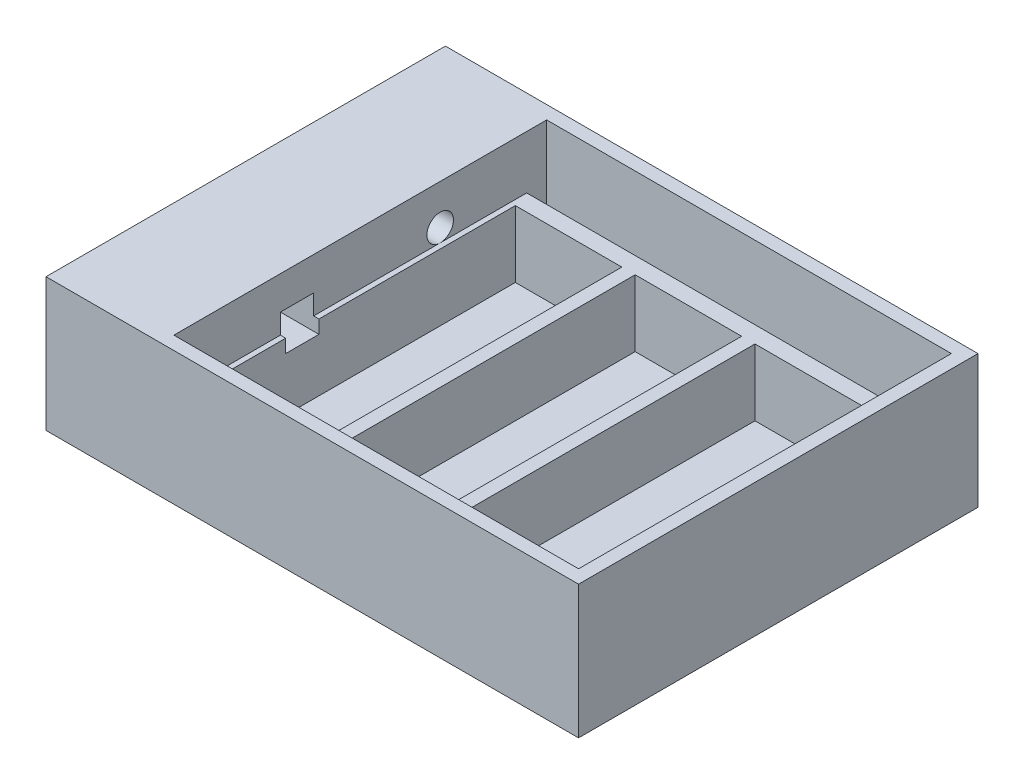
SolidWorks part; units mm, degrees
ref_plane "Front Plane" through (0, 0, 0) normal (0, 0, 1) x (1, 0, 0)
ref_plane "Top Plane" through (0, 0, 0) normal (0, 1, 0) x (1, 0, 0)
ref_plane "Right Plane" through (0, 0, 0) normal (1, 0, 0) x (0, 0, -1)
sketch "Sketch1" plane through (0, 0, 0) normal (0, 1, 0) x (1, 0, 0)
  line L1 (-44.8597, 34.7202) -> (56.7403, 34.7202)
  line L2 (-44.8597, 34.7202) -> (-44.8597, -41.4798)
  line L3 (-44.8597, -41.4798) -> (56.7403, -41.4798)
  line L4 (56.7403, 34.7202) -> (56.7403, -41.4798)
  dimension "D1" = 76.2
  dimension "D2" = 101.6
extrude "Boss-Extrude1" add sketch "Sketch1" along normal blind 25.4
sketch "Sketch2" plane through (0, 25.4, 0) normal (0, 1, 0) x (1, 0, 0)
  line L0 (-44.8597, -41.4798) -> (56.7403, -41.4798) construction
  line L1 (-23.0045, 32.1802) -> (54.2003, 32.1802)
  line L2 (-23.0045, 32.1802) -> (-23.0045, -38.9398)
  line L3 (-23.0045, -38.9398) -> (54.2003, -38.9398)
  line L4 (54.2003, 32.1802) -> (54.2003, -38.9398)
  line L5 (56.7403, 34.7202) -> (-44.8597, 34.7202) construction
  line L6 (56.7403, -41.4798) -> (56.7403, 34.7202) construction
  dimension "D1" = 2.54
  dimension "D2" = 2.54
  dimension "D3" = 2.54
extrude "Cut-Extrude1" cut sketch "Sketch2" against normal blind 22.86
sketch "Sketch3" plane through (0, 2.54, 0) normal (0, 1, 0) x (1, 0, 0)
  line L0 (56.7403, -41.4798) -> (56.7403, 34.7202) construction
  line L1 (-23.0045, 28.3702) -> (50.3903, 28.3702)
  line L2 (-23.0045, 28.3702) -> (-23.0045, -35.1298)
  line L3 (-23.0045, -35.1298) -> (50.3903, -35.1298)
  line L4 (50.3903, 28.3702) -> (50.3903, -35.1298)
  line L5 (56.7403, 34.7202) -> (-44.8597, 34.7202) construction
  line L6 (-44.8597, -41.4798) -> (56.7403, -41.4798) construction
  line L7 (-23.0045, 32.1802) -> (-23.0045, -38.9398) construction
  dimension "D1" = 6.35
  dimension "D2" = 6.35
  dimension "D3" = 6.35
  dimension "D4" = 0
extrude "Boss-Extrude3" add sketch "Sketch3" along normal blind 12.7
sketch "Sketch4" plane through (-44.8597, 0, 0) normal (-1, 0, 0) x (0, 0, 1)
  line L0 (-34.7202, 25.4) -> (-34.7202, 0) construction
  line L1 (-15.6702, 21.59) -> (22.4298, 21.59)
  line L2 (-15.6702, 21.59) -> (-15.6702, 6.35)
  line L3 (-15.6702, 6.35) -> (22.4298, 6.35)
  line L4 (22.4298, 21.59) -> (22.4298, 6.35)
  line L5 (-34.7202, 0) -> (41.4798, 0) construction
  dimension "D1" = 19.05
  dimension "D2" = 38.1
  dimension "D3" = 15.24
  dimension "D4" = 6.35
extrude "Cut-Extrude2" cut sketch "Sketch4" against normal blind 6.35
sketch "Sketch7" plane through (-44.8597, 0, 0) normal (-1, 0, 0) x (0, 0, 1)
  line L0 (22.4298, 21.59) -> (-15.6702, 21.59) construction
  line L1 (-15.6702, 21.59) -> (-15.6702, 6.35) construction
  circle A0 centre (-11.8602, 17.78) radius 2.5355
  dimension "D1" = 3.81
  dimension "D2" = 3.81
extrude "Cut-Extrude3" cut sketch "Sketch7" against normal blind 22.86
sketch "Sketch8" plane through (-38.5097, 0, 0) normal (-1, 0, 0) x (0, 0, 1)
  line L0 (22.4298, 21.59) -> (-15.6702, 21.59) construction
  line L1 (12.2698, 19.05) -> (18.6198, 19.05)
  line L2 (12.2698, 19.05) -> (12.2698, 12.7)
  line L3 (12.2698, 12.7) -> (18.6198, 12.7)
  line L4 (18.6198, 19.05) -> (18.6198, 12.7)
  line L5 (22.4298, 6.35) -> (22.4298, 21.59) construction
  dimension "D1" = 6.35
  dimension "D2" = 6.35
  dimension "D3" = 2.54
  dimension "D4" = 3.81
extrude "Cut-Extrude5" cut sketch "Sketch8" against normal blind 17.78
sketch "Sketch9" plane through (0, 15.24, 0) normal (0, 1, 0) x (1, 0, 0)
  line L0 (-23.0045, -35.1298) -> (50.3903, -35.1298) construction
  line L1 (23.7203, 25.1952) -> (44.0403, 25.1952)
  line L2 (23.7203, 25.1952) -> (23.7203, -31.9548)
  line L3 (23.7203, -31.9548) -> (44.0403, -31.9548)
  line L4 (44.0403, 25.1952) -> (44.0403, -31.9548)
  line L5 (50.3903, -35.1298) -> (50.3903, 28.3702) construction
  dimension "D1" = 20.32
  dimension "D2" = 57.15
  dimension "D3" = 3.175
  dimension "D5" = 6.35
extrude "Cut-Extrude6" cut sketch "Sketch9" against normal blind 12.7
pattern_linear "LPattern1" count 3 spacing 22.86 along (-1, 0, 0) of "Cut-Extrude6"
